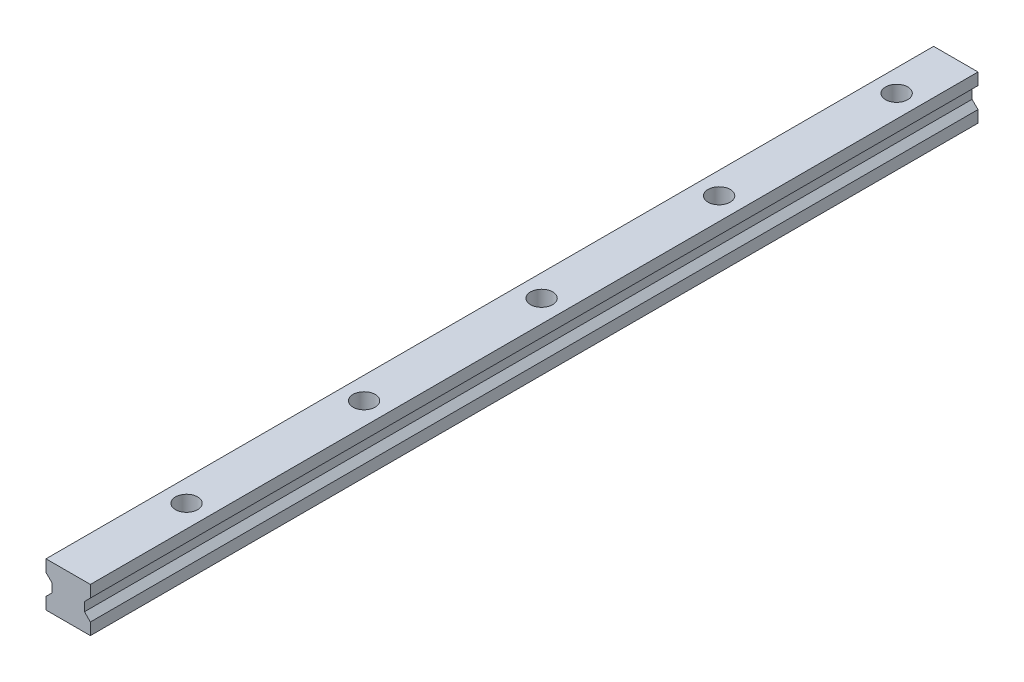
SolidWorks part; units mm, degrees
ref_plane "Front Plane" through (0, 0, 0) normal (0, 0, 1) x (1, 0, 0)
ref_plane "Top Plane" through (0, 0, 0) normal (0, 1, 0) x (1, 0, 0)
ref_plane "Right Plane" through (0, 0, 0) normal (1, 0, 0) x (0, 0, -1)
sketch "Sketch1" plane through (0, 0, 0) normal (0, 0, 1) x (1, 0, 0)
  line L0 (0, 17.31) -> (0, -6.39) construction
  line L1 (-7.5, 0) -> (7.5, 0)
  line L2 (7.5, 0) -> (7.5, 4)
  line L3 (7.5, 4) -> (5.5, 6)
  line L4 (5.5, 6) -> (5.5, 9)
  line L5 (5.5, 9) -> (7.5, 11)
  line L6 (7.5, 11) -> (7.5, 15)
  line L7 (7.5, 15) -> (-7.5, 15)
  line L8 (-7.5, 11) -> (-7.5, 15)
  line L9 (-5.5, 9) -> (-7.5, 11)
  line L10 (-5.5, 6) -> (-5.5, 9)
  line L11 (-7.5, 4) -> (-5.5, 6)
  line L12 (-7.5, 0) -> (-7.5, 4)
  point P11 (0, 15)
  point P17 (0, 0)
  dimension "D1" = 7.5
  dimension "D2" = 15
  dimension "D3" = 4
  dimension "D4" = 4
  dimension "D5" = 45
  dimension "D6" = 45
  dimension "D7" = 3
extrude "Boss-Extrude1" add sketch "Sketch1" along normal blind 300
sketch "Sketch2" plane through (0, 15, 0) normal (0, 1, 0) x (1, 0, 0)
  line L0 (0, 9.6071) -> (0, -39.3975) construction
  circle A0 centre (0, -20) radius 3.75
  circle A1 centre (0, -80) radius 3.75
  circle A2 centre (0, -140) radius 3.75
  circle A3 centre (0, -200) radius 3.75
  circle A4 centre (0, -260) radius 3.75
  dimension "D1" = 7.5
  dimension "D2" = 20
  dimension "D3" = 5
extrude "Cut-Extrude1" cut sketch "Sketch2" against normal blind 5.3
sketch "Sketch3" plane through (0, 15, 0) normal (0, 1, 0) x (1, 0, 0)
  circle A0 centre (0, -20) radius 2.25
  circle A1 centre (0, -80) radius 2.25
  circle A2 centre (0, -140) radius 2.25
  circle A3 centre (0, -200) radius 2.25
  circle A4 centre (0, -260) radius 2.25
  dimension "D1" = 4.5
  dimension "D2" = 5
extrude "Cut-Extrude2" cut sketch "Sketch3" against normal through all
